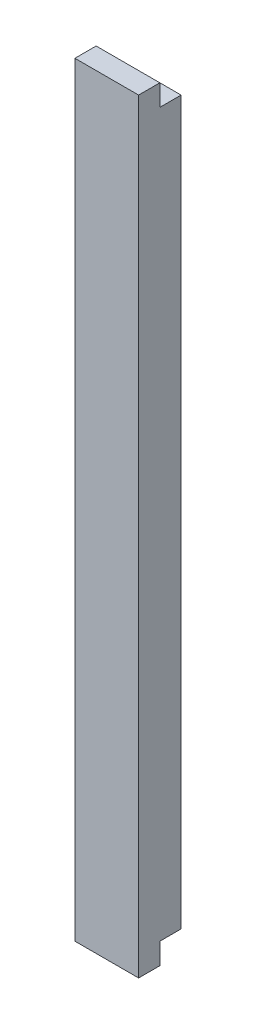
SolidWorks part; units mm, degrees
ref_plane "Front Plane" through (0, 0, 0) normal (0, 0, 1) x (1, 0, 0)
ref_plane "Top Plane" through (0, 0, 0) normal (0, 1, 0) x (1, 0, 0)
ref_plane "Right Plane" through (0, 0, 0) normal (1, 0, 0) x (0, 0, -1)
sketch "Sketch1" plane through (0, 0, 0) normal (0, 0, 1) x (1, 0, 0)
  line L0 (-20, 180) -> (20, 180)
  line L1 (20, 180) -> (20, -180)
  line L2 (20, -180) -> (-20, -180)
  line L3 (-20, -180) -> (-20, 180)
  point P2 (0, 180)
  point P5 (-20, 0)
  dimension "D1" = 40
  dimension "D2" = 360
extrude "Boss-Extrude1" add sketch "Sketch1" along normal blind 20
sketch "Sketch2" plane through (0, 0, 20) normal (0, 0, 1) x (1, 0, 0)
  line L1 (-10, 180) -> (-10, -180)
  line L4 (-20, 180) -> (-20, -180)
  line L5 (-20, -180) -> (20, -180)
  line L6 (20, -180) -> (20, 180)
  line L7 (20, 180) -> (-20, 180)
  line L8 (-20, 180) -> (-20, -180)
  line L9 (-20, -180) -> (-10, -180)
  line L11 (-10, 180) -> (-20, 180)
  line L12 (10, -170) -> (10, 170) construction
  line L13 (10, 170) -> (-10, 170) construction
  line L14 (-10, -170) -> (10, -170) construction
  line L16 (20, -180) -> (20, 180) construction
  line L17 (-10, 170) -> (-10, -170) construction
  line L18 (20, 180) -> (-20, 180) construction
  line L19 (-20, -180) -> (20, -180) construction
  dimension "D1" = 0
  dimension "D2" = 10
extrude "Cut-Extrude1" cut sketch "Sketch2" against normal blind 10
sketch "Sketch3" plane through (0, 0, 0) normal (0, 0, -1) x (-1, 0, 0)
  line L2 (-20, 170) -> (20, 170)
  line L3 (-20, 170) -> (20, 170)
  line L8 (-20, -170) -> (-20, -180)
  line L9 (20, -170) -> (-20, -170)
  line L10 (20, -170) -> (-20, -170)
  line L11 (20, 170) -> (20, 180)
  line L14 (20, -180) -> (20, 180)
  line L15 (20, 180) -> (-20, 180)
  line L16 (-20, 180) -> (-20, -180)
  line L17 (-20, -180) -> (20, -180)
  line L18 (20, -180) -> (20, -170)
  line L19 (20, 180) -> (-20, 180)
  line L20 (-20, 180) -> (-20, 170)
  line L21 (-20, -180) -> (20, -180)
  dimension "D1" = 10
  dimension "D2" = 10
  dimension "D3" = 0
extrude "Cut-Extrude2" cut sketch "Sketch3" against normal blind 10
